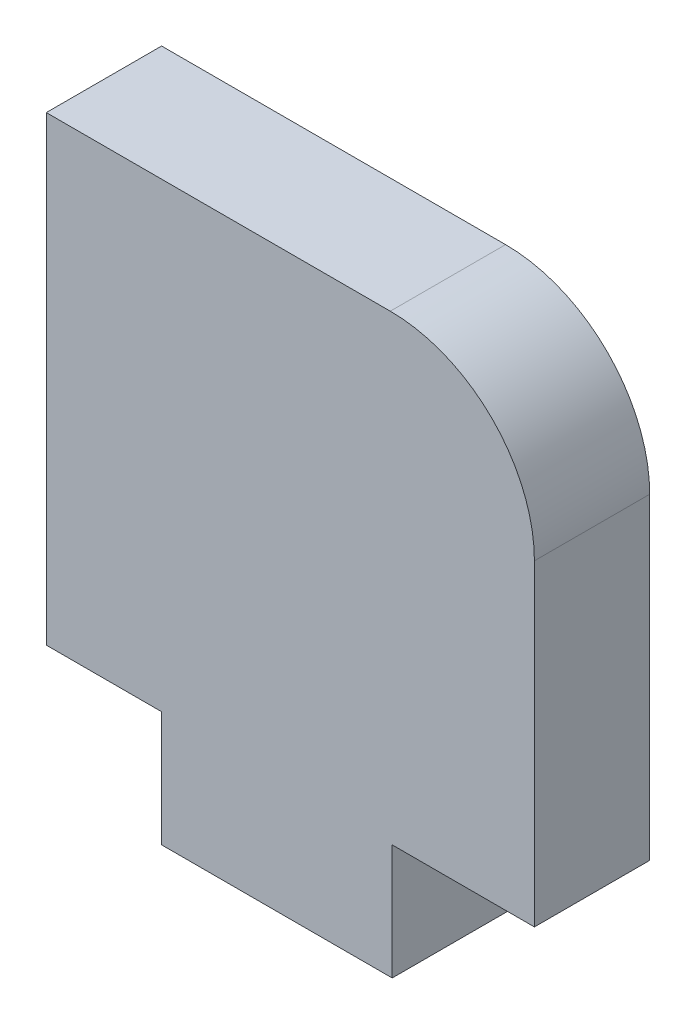
SolidWorks part; units mm, degrees
ref_plane "Front Plane" through (0, 0, 0) normal (0, 0, 1) x (1, 0, 0)
ref_plane "Top Plane" through (0, 0, 0) normal (0, 1, 0) x (1, 0, 0)
ref_plane "Right Plane" through (0, 0, 0) normal (1, 0, 0) x (0, 0, -1)
sketch "Sketch1" plane through (0, 0, 0) normal (0, 0, 1) x (1, 0, 0)
  line L0 (6.0757, -11) -> (11.0089, -11)
  line L1 (-1.9243, -11) -> (-5.9243, -11)
  line L2 (-5.9243, -11) -> (-5.9243, 5)
  line L3 (-5.9243, 5) -> (6.0089, 5)
  line L4 (6.0757, -11) -> (6.0757, -15)
  line L5 (6.0757, -15) -> (-1.9243, -15)
  line L6 (-1.9243, -15) -> (-1.9243, -11)
  line L7 (11.0089, 0) -> (11.0089, -11)
  arc A0 (11.0089, 0) -> (6.0089, 5) centre (6.0089, 0) ccw
  dimension "D1" = 5
  dimension "D2" = 16
  dimension "D3" = 4.9332
  dimension "D4" = 8
  dimension "D5" = 4
extrude "Boss-Extrude1" add sketch "Sketch1" along normal blind 4
